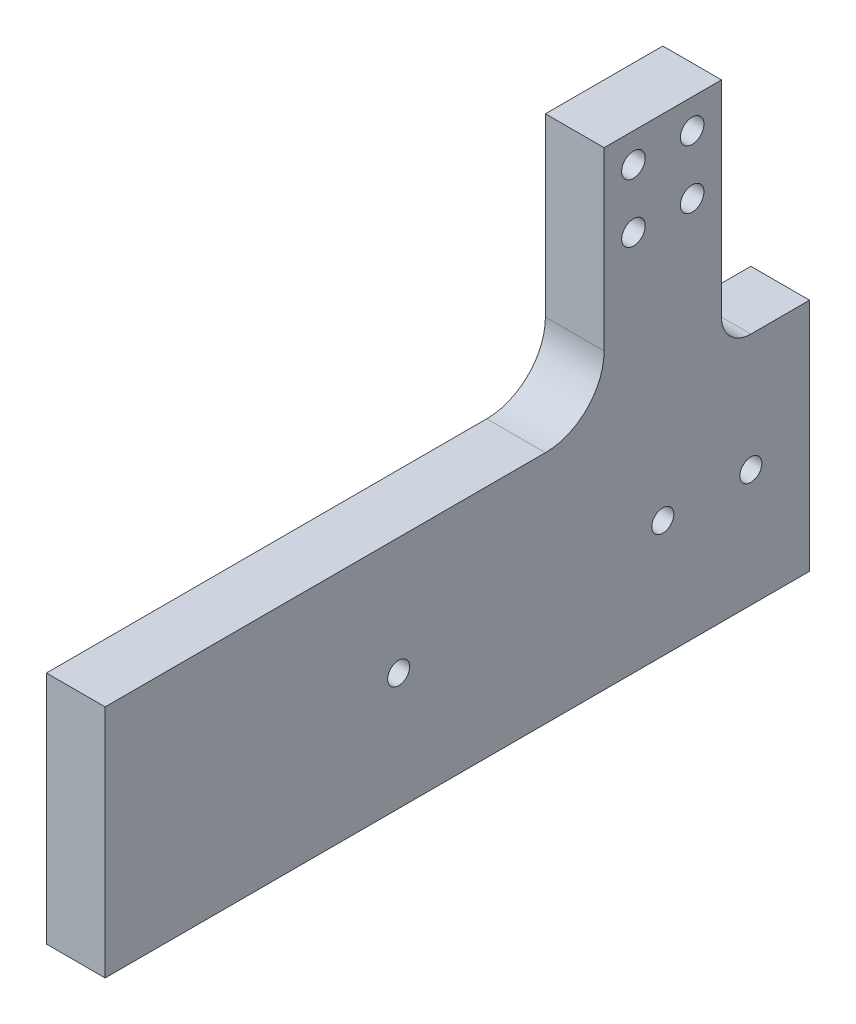
SolidWorks part; units mm, degrees
material "6061-T6 (SS)"
ref_plane "Front Plane" through (0, 0, 0) normal (0, 0, 1) x (1, 0, 0)
ref_plane "Top Plane" through (0, 0, 0) normal (0, 1, 0) x (1, 0, 0)
ref_plane "Right Plane" through (0, 0, 0) normal (1, 0, 0) x (0, 0, -1)
sketch "Sketch1" plane through (0, 0, 0) normal (1, 0, 0) x (0, 0, -1)
  line L1 (-19.05, 101.6) -> (-44.45, 101.6)
  line L2 (-44.45, 101.6) -> (-44.45, 50.8)
  line L3 (-44.45, 50.8) -> (-152.4, 50.8)
  line L4 (-152.4, 50.8) -> (-152.4, 0)
  line L5 (-152.4, 0) -> (0, 0)
  line L6 (-12.7, 25.4) -> (-88.9, 25.4) construction
  line L7 (-19.05, 101.6) -> (-19.05, 50.8)
  line L8 (-19.05, 50.8) -> (0, 50.8)
  line L9 (0, 50.8) -> (0, 0)
  circle A0 centre (-88.9, 25.4) radius 2.3813
  circle A1 centre (-31.75, 25.4) radius 2.3813
  circle A2 centre (-12.7, 25.4) radius 2.3813
  point P15 (-36.611, 50.8)
  point P16 (0, 50.8)
  dimension "D5" = 4.7625
  dimension "D6" = 19.05
  dimension "D1" = 101.6
  dimension "D2" = 152.4
  dimension "D3" = 50.8
  dimension "D4" = 25.4
  dimension "D9" = 25.4
extrude "Boss-Extrude1" add sketch "Sketch1" along normal blind 12.7
hole_wizard "#10 Clearance Hole1" positions "Sketch2" profile "Sketch3" hole size "#10" standard "ANSI Inch" end condition through all
sketch "Sketch2" plane through (12.7, 0, 0) normal (1, 0, 0) x (0, 0, -1)
  line L0 (-44.45, 101.6) -> (-44.45, 50.8) construction
  line L2 (-19.05, 50.8) -> (-19.05, 101.6) construction
  line L3 (-19.05, 101.6) -> (-44.45, 101.6) construction
  point P0 (-38.1, 95.25)
  point P2 (-25.4, 95.25)
  point P4 (-25.4, 82.55)
  point P6 (-38.1, 82.55)
  point P16 (-26.5482, 95.25)
  point P17 (-26.5482, 82.55)
  dimension "D1" = 6.35
  dimension "D2" = 6.35
  dimension "D3" = 6.35
  dimension "D4" = 6.35
  dimension "D5" = 12.7
  dimension "D6" = 12.7
  dimension "D7" = 6.35
  dimension "D8" = 6.35
sketch "Sketch3" plane through (12.7, 95.25, 38.1) normal (0, 1, 0) x (0, 0, -1)
  line L0 (0, 0) -> (0, 12.7)
  line L1 (0, 12.7) -> (2.5527, 12.7)
  line L2 (2.5527, 12.7) -> (2.5527, 0)
  line L5 (2.5527, 0) -> (0, 0)
  line L11 (0, -6.35) -> (0, 107.95) construction
  dimension "Thru Hole Dia." = 5.1054
  dimension "Thru Hole Depth" = 12.7
ref_point "Point1"
ref_point "Point2"
ref_point "Point3"
fillet "Fillet1" radius 12.7 1 edges at (6.35, 50.8, 44.45)
fillet "Fillet2" radius 6.35 1 edges at (6.35, 50.8, 19.05)
